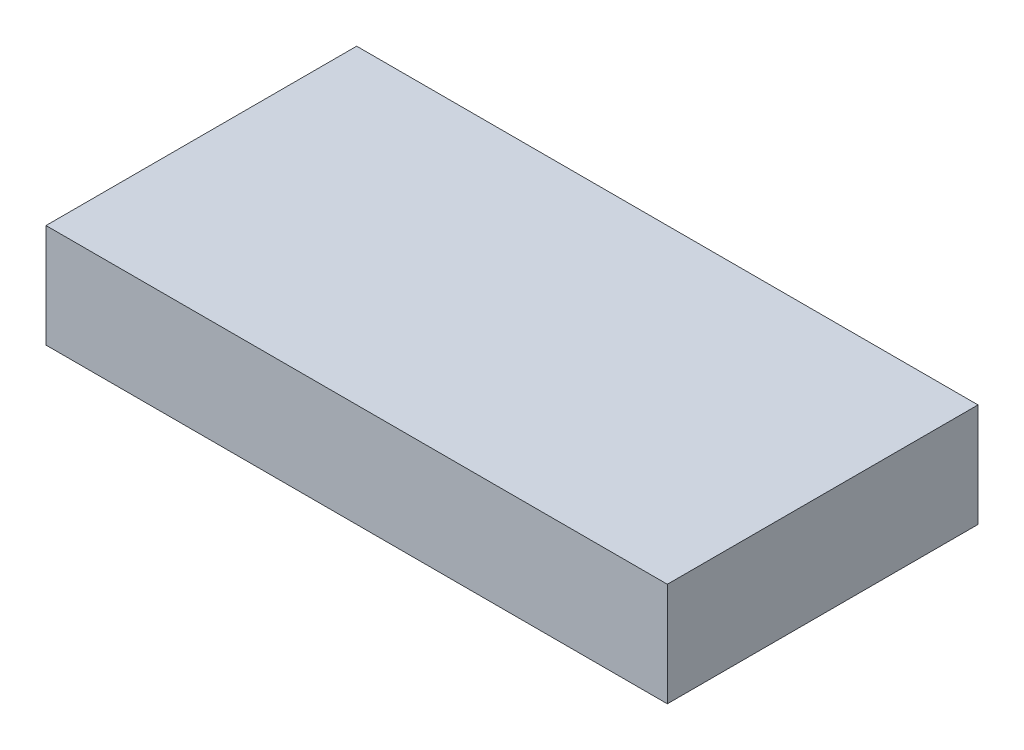
SolidWorks part; units mm, degrees
ref_plane "Front Plane" through (0, 0, 0) normal (0, 0, 1) x (1, 0, 0)
ref_plane "Top Plane" through (0, 0, 0) normal (0, 1, 0) x (1, 0, 0)
ref_plane "Right Plane" through (0, 0, 0) normal (1, 0, 0) x (0, 0, -1)
sketch "Sketch1" plane through (0, 0, 0) normal (0, 1, 0) x (1, 0, 0)
  line L1 (-10.6817, 4.969) -> (13.3183, 4.969)
  line L2 (-10.6817, 4.969) -> (-10.6817, -7.031)
  line L3 (-10.6817, -7.031) -> (13.3183, -7.031)
  line L4 (13.3183, 4.969) -> (13.3183, -7.031)
  dimension "D1" = 24
  dimension "D2" = 12
extrude "Boss-Extrude1" add sketch "Sketch1" along normal blind 4
